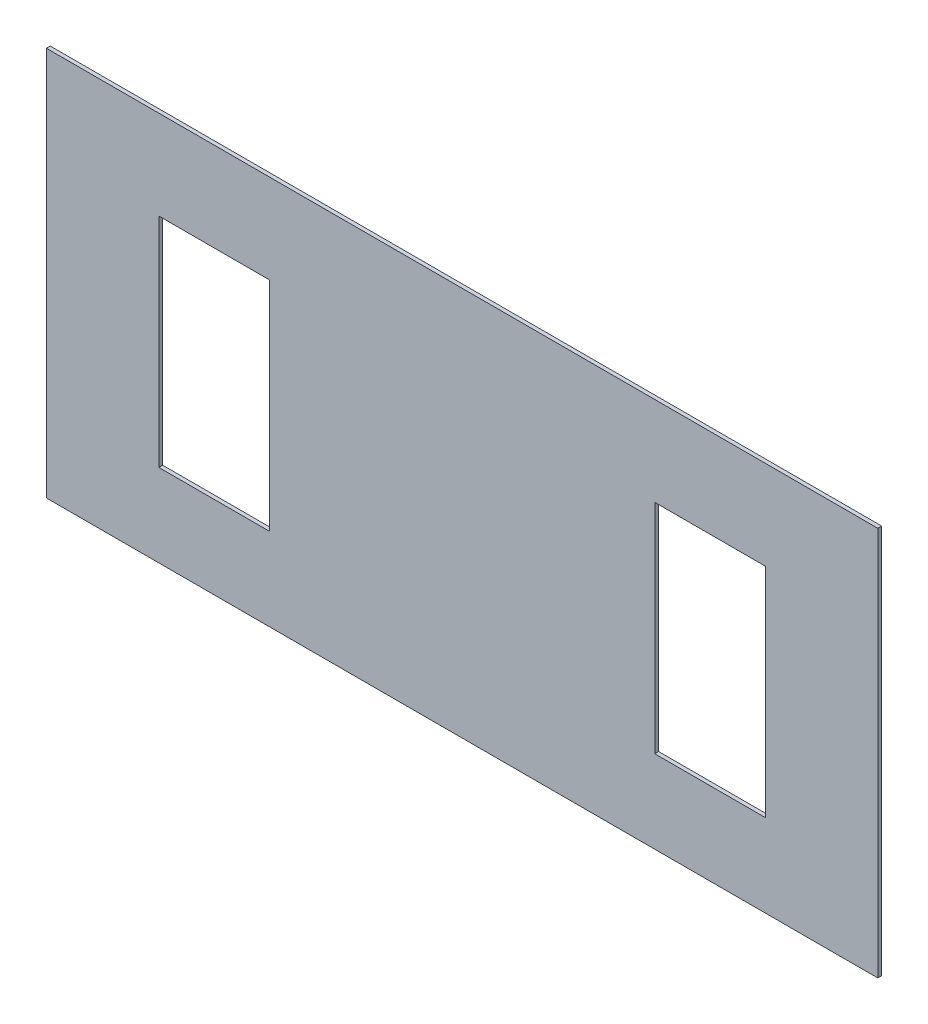
SolidWorks part; units mm, degrees
ref_plane "Front Plane" through (0, 0, 0) normal (0, 0, 1) x (1, 0, 0)
ref_plane "Top Plane" through (0, 0, 0) normal (0, 1, 0) x (1, 0, 0)
ref_plane "Right Plane" through (0, 0, 0) normal (1, 0, 0) x (0, 0, -1)
sketch "Sketch1" plane through (0, 0, 0) normal (0, 0, 1) x (1, 0, 0)
  line L0 (-11.525, -100) -> (-11.525, 103.337)
  line L1 (-11.525, 103.337) -> (422.475, 103.337)
  line L2 (422.475, 103.337) -> (422.475, -100)
  line L3 (422.475, -100) -> (-11.525, -100)
extrude "Boss-Extrude1" add sketch "Sketch1" along normal blind 2
sketch "Sketch2" plane through (0, 0, 2) normal (0, 0, 1) x (1, 0, 0)
  line L0 (205.475, -100) -> (205.475, 103.337) construction
  line L1 (104.8865, -56.8268) -> (47.1635, -56.8268)
  line L2 (104.8865, -56.8268) -> (104.8865, 56.8268)
  line L3 (104.8865, 56.8268) -> (47.1635, 56.8268)
  line L4 (47.1635, -56.8268) -> (47.1635, 56.8268)
  line L5 (104.8865, -56.8268) -> (47.1635, 56.8268) construction
  line L6 (104.8865, 56.8268) -> (47.1635, -56.8268) construction
  line L7 (-11.525, -100) -> (422.475, -100) construction
  line L8 (422.475, 103.337) -> (-11.525, 103.337) construction
  line L9 (306.0635, 56.8268) -> (363.7865, -56.8268) construction
  line L10 (306.0635, -56.8268) -> (363.7865, 56.8268) construction
  line L11 (363.7865, -56.8268) -> (363.7865, 56.8268)
  line L12 (306.0635, 56.8268) -> (363.7865, 56.8268)
  line L13 (306.0635, -56.8268) -> (306.0635, 56.8268)
  line L14 (306.0635, -56.8268) -> (363.7865, -56.8268)
  line L15 (76.025, 85.063) -> (76.025, -84.937) construction
  point P0 (76.025, 0)
  point P15 (334.925, 0)
extrude "Cut-Extrude1" cut sketch "Sketch2" against normal through all
